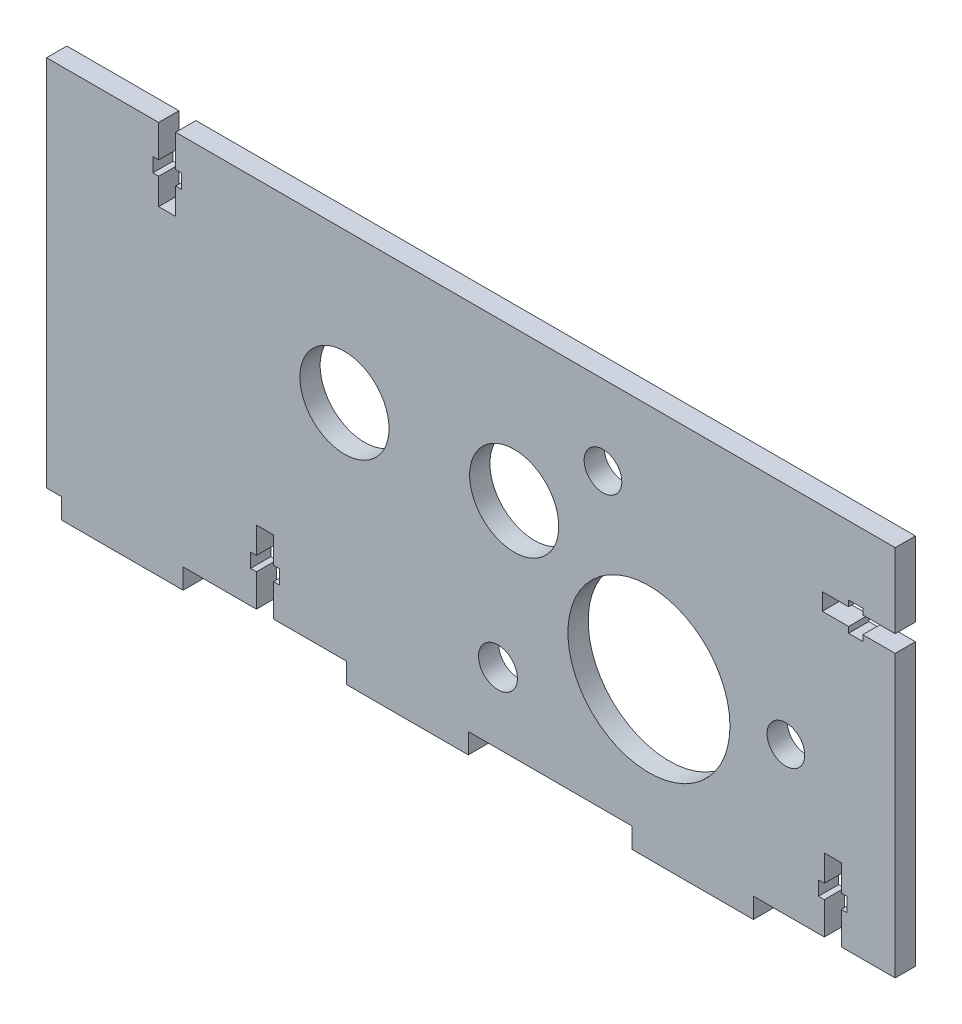
SolidWorks part; units mm, degrees
ref_plane "Front Plane" through (0, 0, 0) normal (0, 0, 1) x (1, 0, 0)
ref_plane "Top Plane" through (0, 0, 0) normal (0, 1, 0) x (1, 0, 0)
ref_plane "Right Plane" through (0, 0, 0) normal (1, 0, 0) x (0, 0, -1)
sketch "Sketch1" plane through (0, 0, 0) normal (0, 0, 1) x (1, 0, 0)
  line L1 (-115, -45) -> (115, -45)
  line L2 (-115, -45) -> (-115, 45)
  line L3 (-115, 45) -> (115, 45)
  line L4 (115, -45) -> (115, 45)
  line L5 (-115, -45) -> (115, 45) construction
  line L6 (-115, 45) -> (115, -45) construction
  point P0 (0, 0)
  dimension "D1" = 230
  dimension "D2" = 90
extrude "Boss-Extrude1" add sketch "Sketch1" along normal blind 5
sketch "Sketch2" plane through (0, 0, 5) normal (0, 0, 1) x (1, 0, 0)
  line L0 (-115, 10) -> (115, 10) construction
  line L1 (-115, 45) -> (-115, -45) construction
  line L2 (115, -45) -> (115, 45) construction
  circle A0 centre (-20.95, 10) radius 11
  circle A1 centre (20.95, 10) radius 11
  circle A2 centre (49.9769, -10) radius 16.75
  dimension "D2" = 22
  dimension "D4" = 33.5
  dimension "D1" = 41.9
  dimension "D3" = 20.95
  dimension "D5" = 35.25
  dimension "D6" = 20
  dimension "D7" = 10
extrude "Cut-Extrude1" cut sketch "Sketch2" against normal up to next
sketch "Sketch3" plane through (0, 0, 0) normal (0, 0, -1) x (-1, 0, 0)
  circle A0 centre (-42.8615, 27.3153) radius 4.65
  circle A1 centre (-88.0159, -8.5603) radius 4.65
  circle A2 centre (-16.9352, -27.6044) radius 4.8
extrude "Cut-Extrude2" cut sketch "Sketch3" against normal up to next
other "Move Face1" face at (0, 45, 2.5) parameters "D1"=2
sketch "Sketch5" plane through (0, 0, 0) normal (0, 0, -1) x (-1, 0, 0)
  line L1 (94.4901, 47) -> (115, 47)
  line L2 (94.4901, 47) -> (94.4901, -79.3849)
  line L3 (94.4901, -79.3849) -> (115, -79.3849)
  line L4 (115, 47) -> (115, -79.3849)
  line L5 (115, 47) -> (115, -45) construction
extrude "Cut-Extrude3" cut sketch "Sketch5" against normal blind 5
sketch "Sketch6" plane through (0, 0, 0) normal (0, 0, -1) x (-1, 0, 0)
  line L4 (20.3912, -45) -> (-9.6088, -45)
  line L5 (-9.6088, -45) -> (-9.6088, -50)
  line L6 (-9.6088, -50) -> (20.3912, -50)
  line L7 (20.3912, -50) -> (20.3912, -45)
  line L8 (20.3912, -45) -> (-9.6088, -45)
  line L9 (-9.6088, -45) -> (-9.6088, -50)
  line L10 (-9.6088, -50) -> (20.3912, -50)
  line L11 (20.3912, -50) -> (20.3912, -45)
  line L12 (90.7824, -45) -> (60.7824, -45)
  line L13 (60.7824, -45) -> (60.7824, -50)
  line L14 (60.7824, -50) -> (90.7824, -50)
  line L15 (90.7824, -50) -> (90.7824, -45)
  line L16 (90.7824, -45) -> (60.7824, -45)
  line L17 (60.7824, -45) -> (60.7824, -50)
  line L18 (60.7824, -50) -> (90.7824, -50)
  line L19 (90.7824, -50) -> (90.7824, -45)
  line L20 (-50, -45) -> (-80, -45)
  line L21 (-50, -50) -> (-50, -45)
  line L22 (-80, -50) -> (-50, -50)
  line L23 (-80, -45) -> (-80, -50)
  line L24 (-50, -45) -> (-80, -45)
  line L25 (-50, -50) -> (-50, -45)
  line L26 (-80, -50) -> (-50, -50)
  line L27 (-80, -45) -> (-80, -50)
  dimension "D1" = 0
  dimension "D2" = 0
  dimension "D3" = 0
extrude "Boss-Extrude3" add sketch "Sketch6" against normal blind 5
sketch "Sketch7" plane through (0, 0, 5) normal (0, 0, 1) x (1, 0, 0)
  line L2 (80, -45) -> (115, -45) construction
  line L3 (115, -45) -> (115, 47) construction
  line L4 (115, 47) -> (-94.4901, 47) construction
  line B0 (-42.6868, -45) -> (-42.6868, -37)
  line B1 (-42.6868, -37) -> (-44.1368, -37)
  line B2 (-44.1368, -37) -> (-44.1368, -33.5)
  line B3 (-44.1368, -33.5) -> (-42.6868, -33.5)
  line B4 (-42.6868, -33.5) -> (-42.6868, -27)
  line B5 (-42.6868, -27) -> (-38.4868, -27)
  line B6 (-38.4868, -45) -> (-42.6868, -45)
  line B7 (-40.5868, -27) -> (-40.5868, -45) construction
  line B8 (-38.4868, -33.5) -> (-38.4868, -27)
  line B9 (-37.0368, -33.5) -> (-38.4868, -33.5)
  line B10 (-37.0368, -37) -> (-37.0368, -33.5)
  line B11 (-38.4868, -37) -> (-37.0368, -37)
  line B12 (-38.4868, -45) -> (-38.4868, -37)
  line B13 (97.5, -45) -> (97.5, -37)
  line B14 (97.5, -37) -> (96.05, -37)
  line B15 (96.05, -37) -> (96.05, -33.5)
  line B16 (96.05, -33.5) -> (97.5, -33.5)
  line B17 (97.5, -33.5) -> (97.5, -27)
  line B18 (97.5, -27) -> (101.7, -27)
  line B19 (101.7, -45) -> (97.5, -45)
  line B20 (101.7, -33.5) -> (101.7, -27)
  line B21 (103.15, -33.5) -> (101.7, -33.5)
  line B22 (103.15, -37) -> (103.15, -33.5)
  line B23 (101.7, -37) -> (103.15, -37)
  line B24 (101.7, -45) -> (101.7, -37)
  line B25 (115, 24.403) -> (107, 24.403)
  line B26 (107, 24.403) -> (107, 22.953)
  line B27 (107, 22.953) -> (103.5, 22.953)
  line B28 (103.5, 22.953) -> (103.5, 24.403)
  line B29 (103.5, 24.403) -> (97, 24.403)
  line B30 (97, 24.403) -> (97, 28.603)
  line B31 (115, 28.603) -> (115, 24.403)
  line B32 (103.5, 28.603) -> (97, 28.603)
  line B33 (103.5, 30.053) -> (103.5, 28.603)
  line B34 (107, 30.053) -> (103.5, 30.053)
  line B35 (107, 28.603) -> (107, 30.053)
  line B36 (115, 28.603) -> (107, 28.603)
  line B37 (-62.6095, 47) -> (-62.6095, 39)
  line B38 (-62.6095, 39) -> (-61.1595, 39)
  line B39 (-61.1595, 39) -> (-61.1595, 35.5)
  line B40 (-61.1595, 35.5) -> (-62.6095, 35.5)
  line B41 (-62.6095, 35.5) -> (-62.6095, 29)
  line B42 (-62.6095, 29) -> (-66.8095, 29)
  line B43 (-66.8095, 47) -> (-62.6095, 47)
  line B44 (-66.8095, 35.5) -> (-66.8095, 29)
  line B45 (-68.2595, 35.5) -> (-66.8095, 35.5)
  line B46 (-68.2595, 39) -> (-68.2595, 35.5)
  line B47 (-66.8095, 39) -> (-68.2595, 39)
  line B48 (-66.8095, 47) -> (-66.8095, 39)
sketch_block_instance "Block1-1"
sketch_block "Block1" parameters "D1"=2.1, "D2"=3.55, "D3"=3.5
sketch_block_instance "Block1-2"
sketch_block_instance "Block1-3"
sketch_block_instance "Block1-4"
extrude "Cut-Extrude4" cut sketch "Sketch7" against normal blind 10
sketch "Sketch8" plane through (0, 0, 5) normal (0, 0, 1) x (1, 0, 0)
  circle B0 centre (54.2136, -11.5176) radius 20
  circle B1 centre (42.8615, 27.3153) radius 4.65
  circle B2 centre (88.0159, -8.5603) radius 4.65
  circle B3 centre (16.9352, -27.6044) radius 4.8
  circle B4 centre (20.95, 10) radius 11
  circle B5 centre (-20.95, 10) radius 11
sketch_block_instance "Block2-1"
sketch_block "Block2"
sketch "Sketch9" plane through (0, 0, 5) normal (0, 0, 1) x (1, 0, 0)
  line L0 (-39.5849, 23.4108) -> (-37.5231, -9.5781)
  line L1 (-37.5231, -9.5781) -> (-6.5961, -20.918)
  line L2 (-6.5961, -20.918) -> (6.5994, -35.9691)
  line L3 (6.5994, -35.9691) -> (51.7529, -37.6185)
  line L4 (51.7529, -37.6185) -> (87.6282, -20.918)
  line L5 (87.6282, -20.918) -> (101.8546, 0)
  line L6 (101.8546, 0) -> (47.0849, 37.2492)
  line L7 (47.0849, 37.2492) -> (-39.5849, 23.4108)
extrude "Boss-Extrude4" add sketch "Sketch9" against normal blind 5
extrude "Cut-Extrude5" cut sketch "Sketch8" against normal blind 5
